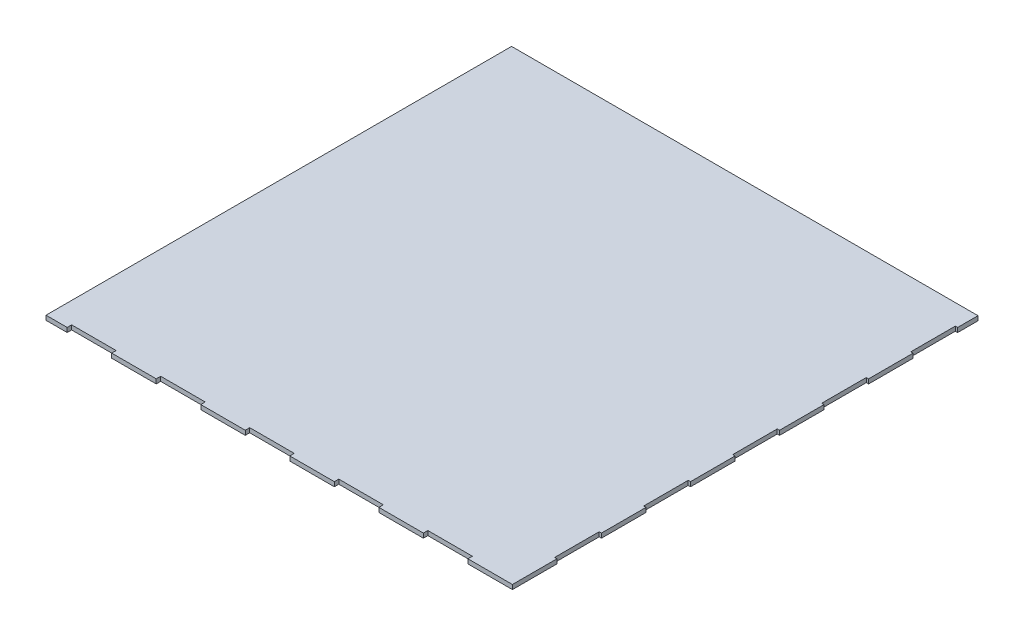
SolidWorks part; units mm, degrees
ref_plane "Front Plane" through (0, 0, 0) normal (0, 0, 1) x (1, 0, 0)
ref_plane "Top Plane" through (0, 0, 0) normal (0, 1, 0) x (1, 0, 0)
ref_plane "Right Plane" through (0, 0, 0) normal (1, 0, 0) x (0, 0, -1)
sketch "Sketch1" plane through (0, 0, 0) normal (0, 1, 0) x (1, 0, 0)
  line L1 (-315, -315) -> (315, -315)
  line L2 (-315, -315) -> (-315, 315)
  line L3 (-315, 315) -> (315, 315)
  line L4 (315, -315) -> (315, 315)
  line L5 (0, 315) -> (0, -315) construction
  line L6 (-315, 0) -> (315, 0) construction
  point P0 (0, 0)
extrude "Boss-Extrude1" add sketch "Sketch1" along normal blind 3
ref_plane "Plane1" through (0, 0, 285) normal (0, 0, 1) x (1, 0, 0)
sketch "Sketch3" plane through (0, 3, 0) normal (0, 1, 0) x (1, 0, 0)
  line L0 (-315, 315) -> (-315, -315) construction
  line L1 (-315, -285.0068) -> (-312, -285.0068)
  line L2 (-315, -285.0068) -> (-315, -255.0068)
  line L3 (-315, -255.0068) -> (-312, -255.0068)
  line L4 (-312, -285.0068) -> (-312, -255.0068)
  dimension "D1" = 30
  dimension "D2" = 3
extrude "Cut-Extrude2" cut sketch "Sketch3" against normal blind 3
pattern_linear "LPattern2" count 10 spacing 60 along (0, 0, -1) of "Cut-Extrude2"
ref_plane "Plane2" through (0.72, 0, 0) normal (1, 0, 0) x (0, 0, -1)
mirror "Mirror1" about plane through (0.72, 0, 0) normal (1, 0, 0) of "LPattern2", "Cut-Extrude2"
ref_plane "Plane3" through (-285, 0, 0) normal (-1, 0, 0) x (0, 0, 1)
sketch "Sketch5" plane through (0, 3, 0) normal (0, 1, 0) x (1, 0, 0)
  line L0 (-315, -315) -> (315, -315) construction
  line L1 (-285.0003, -315) -> (-255.0003, -315)
  line L2 (-285.0003, -315) -> (-285.0003, -312)
  line L3 (-285.0003, -312) -> (-255.0003, -312)
  line L4 (-255.0003, -315) -> (-255.0003, -312)
  dimension "D1" = 30
  dimension "D2" = 3
extrude "Cut-Extrude3" cut sketch "Sketch5" against normal blind 3
pattern_linear "LPattern3" count 10 spacing 60 along (1, 0, 0) of "Cut-Extrude3"
ref_plane "Plane4" through (0, 0, 1.295) normal (0, 0, 1) x (1, 0, 0)
mirror "Mirror2" about plane through (0, 0, 1.295) normal (0, 0, 1) of "LPattern3", "Cut-Extrude3"
other "SurfaceCut1"
other "SurfaceCut2"
